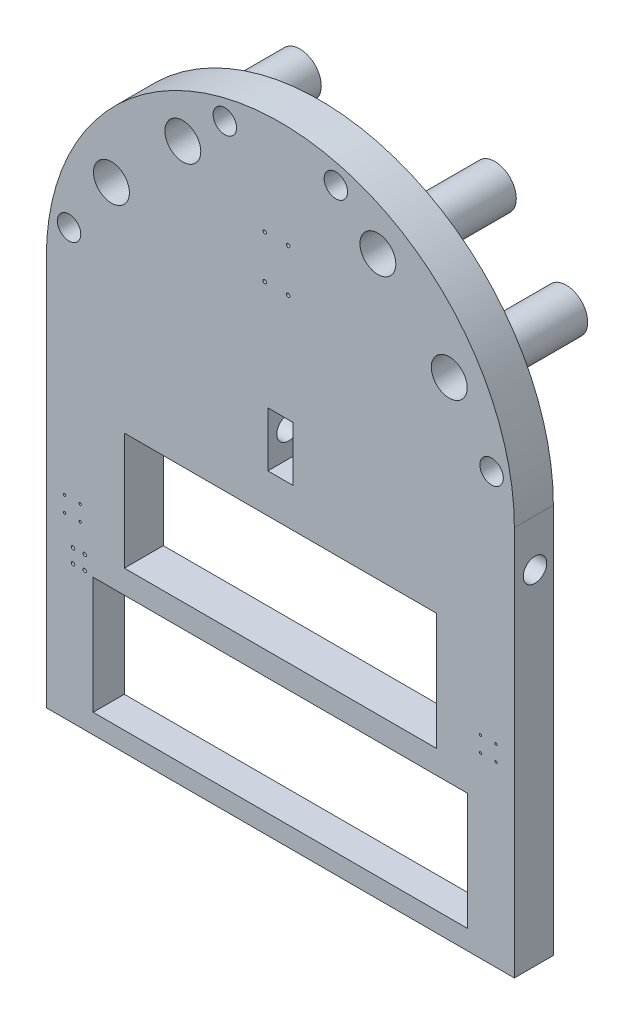
SolidWorks part; units mm, degrees
ref_plane "前视基准面" through (0, 0, 0) normal (0, 0, 1) x (1, 0, 0)
ref_plane "上视基准面" through (0, 0, 0) normal (0, 1, 0) x (1, 0, 0)
ref_plane "右视基准面" through (0, 0, 0) normal (1, 0, 0) x (0, 0, -1)
sketch "草图1" plane through (0, 0, 0) normal (0, 0, 1) x (1, 0, 0)
  line L0 (0, 0) -> (0, 283.2621) construction
  line L1 (0, 0) -> (-125, 216.5064) construction
  line L2 (0, 0) -> (-216.5064, 125) construction
  line L3 (-300, 0) -> (-300, -500)
  line L4 (-300, -500) -> (300, -500)
  line L5 (300, -500) -> (300, 0)
  arc A0 (300, 0) -> (-300, 0) centre (0, 0) ccw
  circle A1 centre (0, 0) radius 250 construction
  circle A2 centre (-216.5064, 125) radius 23
  circle A3 centre (-125, 216.5064) radius 23
  circle A4 centre (125, 216.5064) radius 23
  circle A5 centre (216.5064, 125) radius 23
  dimension "D1" = 300
  dimension "D2" = 500
  dimension "D5" = 46
  dimension "D6" = 46
  dimension "D7" = 500
  dimension "D3" = 30
  dimension "D4" = 30
extrude "凸台-拉伸1" add sketch "草图1" along normal blind 50
sketch "草图2" plane through (0, 0, 0) normal (0, 0, -1) x (-1, 0, 0)
  line L0 (0, 0) -> (0, 105.4108) construction
  circle A0 centre (-216.5064, 125) radius 23
  circle A1 centre (-125, 216.5064) radius 23
  circle A2 centre (-216.5064, 125) radius 27.5
  circle A3 centre (-125, 216.5064) radius 27.5
  circle A4 centre (216.5064, 125) radius 27.5
  circle A5 centre (216.5064, 125) radius 23
  circle A6 centre (125, 216.5064) radius 27.5
  circle A7 centre (125, 216.5064) radius 23
  dimension "D1" = 55
  dimension "D2" = 55
extrude "凸台-拉伸2" add sketch "草图2" along normal blind 100
sketch "草图3" plane through (-300, 0, 0) normal (-1, 0, 0) x (0, 0, 1)
  line L0 (50, 0) -> (0, 0) construction
  circle A0 centre (23.5483, -60) radius 15
  dimension "D2" = 30
  dimension "D1" = 60
extrude "切除-拉伸1" cut sketch "草图3" against normal through all
sketch "草图4" plane through (0, 0, 50) normal (0, 0, 1) x (1, 0, 0)
  line L1 (-16, -25) -> (16, -25)
  line L2 (-16, -25) -> (-16, -95)
  line L3 (-16, -95) -> (16, -95)
  line L4 (16, -25) -> (16, -95)
  line L5 (0, -95) -> (0, -25) construction
  line L6 (-16, -60) -> (16, -60) construction
  point P0 (0, -60)
  dimension "D1" = 60
  dimension "D2" = 70
  dimension "32" = 32
extrude "切除-拉伸2" cut sketch "草图4" against normal blind 100
sketch "草图5" plane through (0, 0, 50) normal (0, 0, 1) x (1, 0, 0)
  line L1 (-200, -145) -> (200, -145)
  line L2 (-200, -145) -> (-200, -295)
  line L3 (-200, -295) -> (200, -295)
  line L4 (200, -145) -> (200, -295)
  line L5 (0, -295) -> (0, -145) construction
  line L6 (-200, -220) -> (200, -220) construction
  point P0 (0, -220)
  dimension "D1" = 150
  dimension "D2" = 400
  dimension "D3" = 220
extrude "切除-拉伸3" cut sketch "草图5" against normal through all
sketch "草图6" plane through (0, 0, 50) normal (0, 0, 1) x (1, 0, 0)
  line L1 (-240, -325) -> (240, -325)
  line L2 (-240, -325) -> (-240, -475)
  line L3 (-240, -475) -> (240, -475)
  line L4 (240, -325) -> (240, -475)
  line L5 (0, -475) -> (0, -325) construction
  line L6 (-240, -400) -> (240, -400) construction
  point P0 (0, -400)
  dimension "D1" = 150
  dimension "D2" = 480
  dimension "D3" = 400
extrude "切除-拉伸4" cut sketch "草图6" against normal blind 100
sketch "草图7" plane through (0, 0, 0) normal (0, 0, -1) x (-1, 0, 0)
  line L0 (240, -325) -> (240, -475) construction
  line L1 (-250, -315) -> (250, -315)
  line L2 (-250, -315) -> (-250, -485)
  line L3 (-250, -485) -> (250, -485)
  line L4 (250, -315) -> (250, -485)
  line L5 (0, -485) -> (0, -315) construction
  line L6 (-250, -400) -> (250, -400) construction
  line L7 (240, -475) -> (-240, -475) construction
  line L8 (-240, -325) -> (240, -325) construction
  line L9 (-240, -475) -> (-240, -325) construction
  point P0 (0, -400)
  dimension "D1" = 10
  dimension "D2" = 10
  dimension "D3" = 10
  dimension "D4" = 10
extrude "切除-拉伸5" cut sketch "草图7" against normal blind 10
sketch "草图8" plane through (0, 0, 50) normal (0, 0, 1) x (1, 0, 0)
  line L0 (0, 300) -> (0, -500)
  line L1 (-300, -500) -> (300, -500) construction
  arc A0 (300, 0) -> (-300, 0) centre (0, 0) ccw construction
  point P7 (0, 80)
  dimension "D1" = 80
sketch "草图9" plane through (0, 0, 50) normal (0, 0, 1) x (1, 0, 0)
  circle A0 centre (10, 113.0435) radius 2.25
  circle A1 centre (-20, 113.0435) radius 2.25
  circle A2 centre (-20, 168.2057) radius 2.25
  circle A3 centre (10, 168.2057) radius 2.25
extrude "切除-拉伸6" cut sketch "草图9" against normal blind 5
sketch "草图10" plane through (0, 0, 50) normal (0, 0, 1) x (1, 0, 0)
  line L0 (0, 0) -> (-109.4264, 0) construction
  line L1 (0, 0) -> (0, 103.0554) construction
  line L2 (-270.8221, 47.7532) -> (0, 0) construction
  line L3 (-71.1752, 265.6296) -> (0, 0) construction
  circle A0 centre (0, 0) radius 275 construction
  circle A1 centre (-270.8221, 47.7532) radius 15
  circle A2 centre (-71.1752, 265.6296) radius 15
  circle A3 centre (270.8221, 47.7532) radius 15
  circle A4 centre (71.1752, 265.6296) radius 15
  dimension "D1" = 550
  dimension "D4" = 30
  dimension "D5" = 30
  dimension "D2" = 10
  dimension "D3" = 15
extrude "切除-拉伸7" cut sketch "草图10" against normal blind 30
sketch "草图11" plane through (0, 0, 50) normal (0, 0, 1) x (1, 0, 0)
  circle A0 centre (-265.778, -305.1573) radius 2.25
  circle A1 centre (-250.778, -305.1573) radius 2.25
  circle A2 centre (-265.778, -322.9573) radius 2.25
  circle A3 centre (-250.778, -322.9573) radius 2.25
extrude "切除-拉伸8" cut sketch "草图11" against normal blind 30
sketch "草图12" plane through (0, 0, 50) normal (0, 0, 1) x (1, 0, 0)
  circle A0 centre (-276.543, -251.9641) radius 1.5
  circle A1 centre (-256.543, -251.9641) radius 1.5
  circle A2 centre (-276.543, -271.9641) radius 1.5
  circle A3 centre (-256.543, -271.9641) radius 1.5
extrude "切除-拉伸9" cut sketch "草图12" against normal blind 10
mirror "镜向1" about plane through (0, 0, 0) normal (1, 0, 0) of "切除-拉伸9"
sketch "草图13" plane through (0, 0, 0) normal (0, 0, -1) x (-1, 0, 0)
  circle A0 centre (259.1674, -123.9236) radius 1.5
  circle A1 centre (234.1674, -123.9236) radius 1.5
  circle A2 centre (234.1674, -148.9236) radius 1.5
  circle A3 centre (259.1674, -148.9236) radius 1.5
extrude "切除-拉伸10" cut sketch "草图13" against normal blind 10
